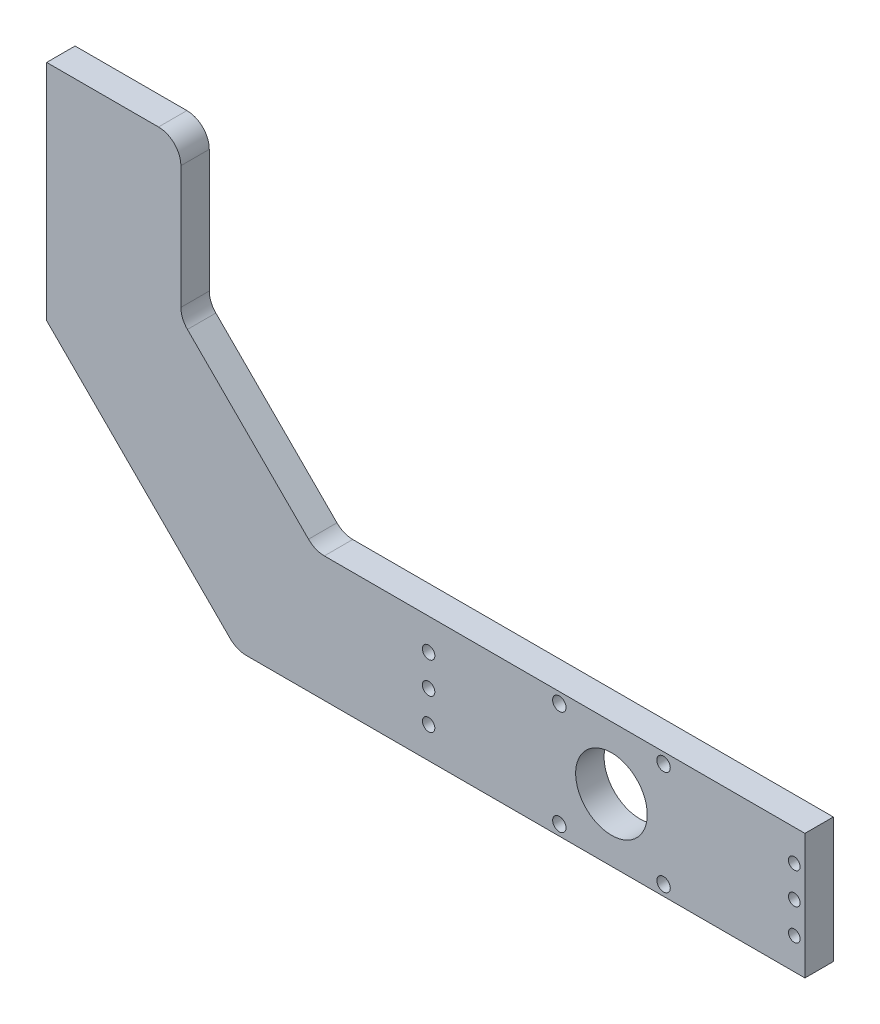
SolidWorks part; units mm, degrees
ref_plane "Plano frontal" through (0, 0, 0) normal (0, 0, 1) x (1, 0, 0)
ref_plane "Plano superior" through (0, 0, 0) normal (0, 1, 0) x (1, 0, 0)
ref_plane "Plano direito" through (0, 0, 0) normal (1, 0, 0) x (0, 0, -1)
sketch "Esboço1" plane through (0, 0, 0) normal (0, 0, 1) x (1, 0, 0)
  line L0 (-114.286, -92.024) -> (224.714, -92.024)
  line L1 (-54.286, 92.976) -> (-114.286, 92.976)
  line L2 (-114.286, 92.976) -> (-114.286, -92.024)
  line L3 (-54.286, 23.976) -> (-54.286, -36.024) construction
  line L4 (-54.286, -36.024) -> (5.714, -36.024) construction
  line L5 (-54.286, 92.976) -> (-54.286, 23.976)
  line L6 (224.714, -92.024) -> (224.714, -36.024)
  line L7 (224.714, -36.024) -> (5.714, -36.024)
  line L8 (5.714, -36.024) -> (-54.286, 23.976)
  dimension "D1" = 219
  dimension "D2" = 56
  dimension "D3" = 339
  dimension "D4" = 185
  dimension "D5" = 60
extrude "Ressalto-extrusão1" add sketch "Esboço1" along normal blind 12.7
sketch "Esboço3" plane through (0, 0, 12.7) normal (0, 0, 1) x (1, 0, 0)
  circle A1 centre (138.214, -64.024) radius 16
  dimension "D1" = 32
  dimension "D2" = 86.5
  dimension "D3" = 28
extrude "circulo de rolamento" cut sketch "Esboço3" against normal up to next
sketch "Esboço5" plane through (0, 0, 12.7) normal (0, 0, 1) x (1, 0, 0)
  line L0 (138.214, -48.024) -> (138.214, -80.024) construction
  line L1 (122.214, -64.024) -> (154.214, -64.024) construction
  line L3 (161.514, -40.724) -> (114.914, -40.724) construction
  line L4 (161.514, -40.724) -> (161.514, -87.324) construction
  line L5 (161.514, -87.324) -> (114.914, -87.324) construction
  line L6 (114.914, -40.724) -> (114.914, -87.324) construction
  circle A0 centre (114.914, -40.724) radius 3
  circle A1 centre (161.514, -40.724) radius 3
  circle A2 centre (161.514, -87.324) radius 3
  circle A3 centre (114.914, -87.324) radius 3
  circle A4 centre (138.214, -64.024) radius 16 construction
  dimension "D1" = 23.3
  dimension "D4" = 23.3
  dimension "D5" = 6
extrude "Corte-extrusão3" cut sketch "Esboço5" against normal up to next
sketch "Esboço6" plane through (-114.286, 0, 0) normal (-1, 0, 0) x (0, 0, 1)
  line L0 (4.765, 92.976) -> (4.765, -7.024) construction
  line L3 (0, 92.976) -> (0, -92.024) construction
  circle A0 centre (4.765, 67.976) radius 2.5
  circle A1 centre (4.765, 42.976) radius 2.5
  circle A2 centre (4.765, 17.976) radius 2.5
  dimension "D1" = 5
  dimension "D2" = 5
  dimension "D3" = 5
  dimension "D4" = 25
  dimension "D5" = 25
  dimension "D6" = 4.765
extrude "Corte-extrusão4" cut sketch "Esboço6" against normal blind 30
sketch "Esboço9" plane through (0, 0, 12.7) normal (0, 0, 1) x (1, 0, 0)
  line L0 (-29.286, -92.024) -> (-114.286, -7.024)
  line L1 (-114.286, -92.024) -> (224.714, -92.024) construction
  line L2 (-114.286, 92.976) -> (-114.286, -92.024) construction
  line L3 (-114.286, -7.024) -> (-114.286, -92.024)
  line L4 (-114.286, -92.024) -> (-29.286, -92.024)
  dimension "D1" = 45
  dimension "D2" = 100
extrude "Corte-extrusão6" cut sketch "Esboço9" against normal up to next
sketch "Esboço10" plane through (0, 0, 12.7) normal (0, 0, 1) x (1, 0, 0)
  line L3 (56.474, -78.024) -> (56.474, -50.024) construction
  line L4 (224.714, -92.024) -> (224.714, -36.024) construction
  line L5 (224.714, -36.024) -> (5.714, -36.024) construction
  line L6 (-29.286, -92.024) -> (224.714, -92.024) construction
  circle A0 centre (56.474, -50.024) radius 2.78
  circle A1 centre (56.474, -64.024) radius 2.78
  circle A2 centre (56.474, -78.024) radius 2.78
  dimension "D1" = 5.56
  dimension "D2" = 5.56
  dimension "D3" = 5.56
  dimension "D4" = 14
  dimension "D5" = 28
  dimension "D7" = 168.24
extrude "Corte-extrusão7" cut sketch "Esboço10" against normal up to next
sketch "Esboço12" plane through (0, 0, 12.7) normal (0, 0, 1) x (1, 0, 0)
  line L0 (219.954, -36.024) -> (219.954, -92.024) construction
  line L1 (224.714, -36.024) -> (5.714, -36.024) construction
  line L2 (-29.286, -92.024) -> (224.714, -92.024) construction
  line L3 (224.714, -92.024) -> (224.714, -36.024) construction
  circle A0 centre (219.954, -50.024) radius 2.6
  circle A1 centre (219.954, -64.024) radius 2.6
  circle A2 centre (219.954, -78.024) radius 2.6
  dimension "D2" = 5.2
  dimension "D3" = 5.2
  dimension "D4" = 5.2
  dimension "D1" = 4.76
  dimension "D5" = 14
  dimension "D6" = 14
extrude "Corte-extrusão8" cut sketch "Esboço12" against normal up to next
fillet "Filete1" radius 10 4 edges at (-54.286, 23.976, 6.35) (5.714, -36.024, 6.35) (-29.286, -92.024, 6.35) (-54.286, 92.976, 6.35)
